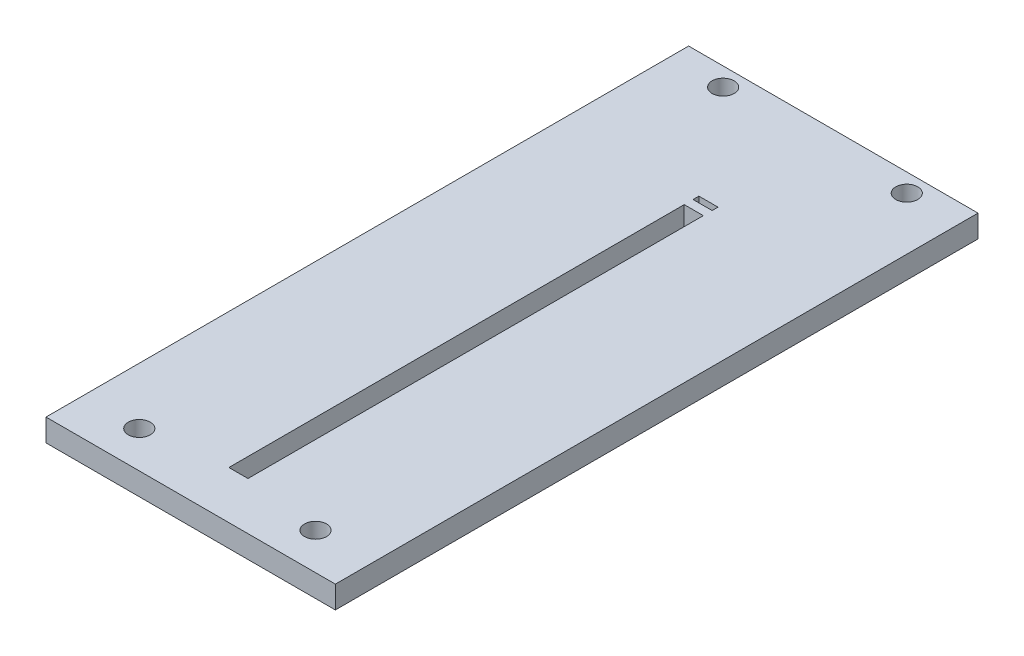
SolidWorks part; units mm, degrees
ref_plane "Front Plane" through (0, 0, 0) normal (0, 0, 1) x (1, 0, 0)
ref_plane "Top Plane" through (0, 0, 0) normal (0, 1, 0) x (1, 0, 0)
ref_plane "Right Plane" through (0, 0, 0) normal (1, 0, 0) x (0, 0, -1)
sketch "Sketch1" plane through (0, 0, 0) normal (0, 1, 0) x (1, 0, 0)
  line L1 (-19.7, 0) -> (19.7, 0)
  line L2 (-19.7, 0) -> (-19.7, 87.5)
  line L3 (-19.7, 87.5) -> (19.7, 87.5)
  line L4 (19.7, 0) -> (19.7, 87.5)
  point P5 (0, 0)
  dimension "D1" = 39.4
  dimension "D2" = 87.5
extrude "Boss-Extrude1" add sketch "Sketch1" along normal blind 3.05
sketch "Sketch4" plane through (0, 3.05, 0) normal (0, 1, 0) x (1, 0, 0)
  line L0 (-19.7, 87.5) -> (19.7, 87.5) construction
  line L2 (-19.7, 0) -> (19.7, 0) construction
  line L3 (1.3, 70.5) -> (-1.3, 70.5)
  line L4 (-1.3, 70.5) -> (-1.3, 69.7)
  line L5 (-1.3, 69.7) -> (1.3, 69.7)
  line L6 (1.3, 69.7) -> (1.3, 70.5)
  line L7 (0, 0) -> (0, 87.5) construction
  line L9 (1.3, 68.5) -> (-1.3, 68.5)
  line L10 (-1.3, 68.5) -> (-1.3, 6.5)
  line L11 (-1.3, 6.5) -> (1.3, 6.5)
  line L12 (1.3, 6.5) -> (1.3, 68.5)
  point P6 (0, 6.5)
  point P10 (0, 70.5)
  point P22 (0, 68.5)
  dimension "D1" = 17
  dimension "D2" = 0.8
  dimension "D3" = 1.2
  dimension "D4" = 2.6
  dimension "D7" = 6.5
extrude "Cut-Extrude1" cut sketch "Sketch4" against normal through all contours L5 L7 L3 L4 | L11 L7 L9 L10 | L7 L11 L12 L9 | L7 L5 L6 L3
sketch "Sketch7" plane through (0, 3.05, 0) normal (0, 1, 0) x (1, 0, 0)
  line L0 (0, 0) -> (-12, 0)
  line L1 (-19.7, 0) -> (19.7, 0) construction
  line L2 (-12, 0) -> (-12, 5)
  line L4 (0, 0) -> (0, 70) construction
  circle A0 centre (-12, 5) radius 1.5
  circle A2 centre (12, 5) radius 1.5
  dimension "D3" = 3
  dimension "D1" = 12
  dimension "D2" = 5
extrude "Cut-Extrude4" cut sketch "Sketch7" against normal through all
hole_wizard "Ø3.0mm Dowel Hole1" positions "Sketch8" profile "Sketch9" hole size "Ø3.0" standard "ANSI Metric" end condition through all
sketch "Sketch8" plane through (0, 3.05, 0) normal (0, 1, 0) x (1, 0, 0)
  line L0 (0, 87.5332) -> (0, 2.5332) construction
  line L3 (-19.7, 87.5) -> (19.7, 87.5) construction
  point P0 (-12.5, 85)
  point P2 (12.5, 85)
  dimension "D1" = 12.5
  dimension "D2" = 2.5
sketch "Sketch9" plane through (-12.5, 3.05, -85) normal (1, 0, 0) x (0, 0, 1)
  line L0 (0, 0) -> (0, 3.05)
  line L1 (0, 3.05) -> (1.5, 3.05)
  line L2 (1.5, 3.05) -> (1.5, 0)
  line L5 (1.5, 0) -> (0, 0)
  line L11 (0, -6.35) -> (0, 107.95) construction
  dimension "Thru Hole Dia." = 3
  dimension "Thru Hole Depth" = 3.05
